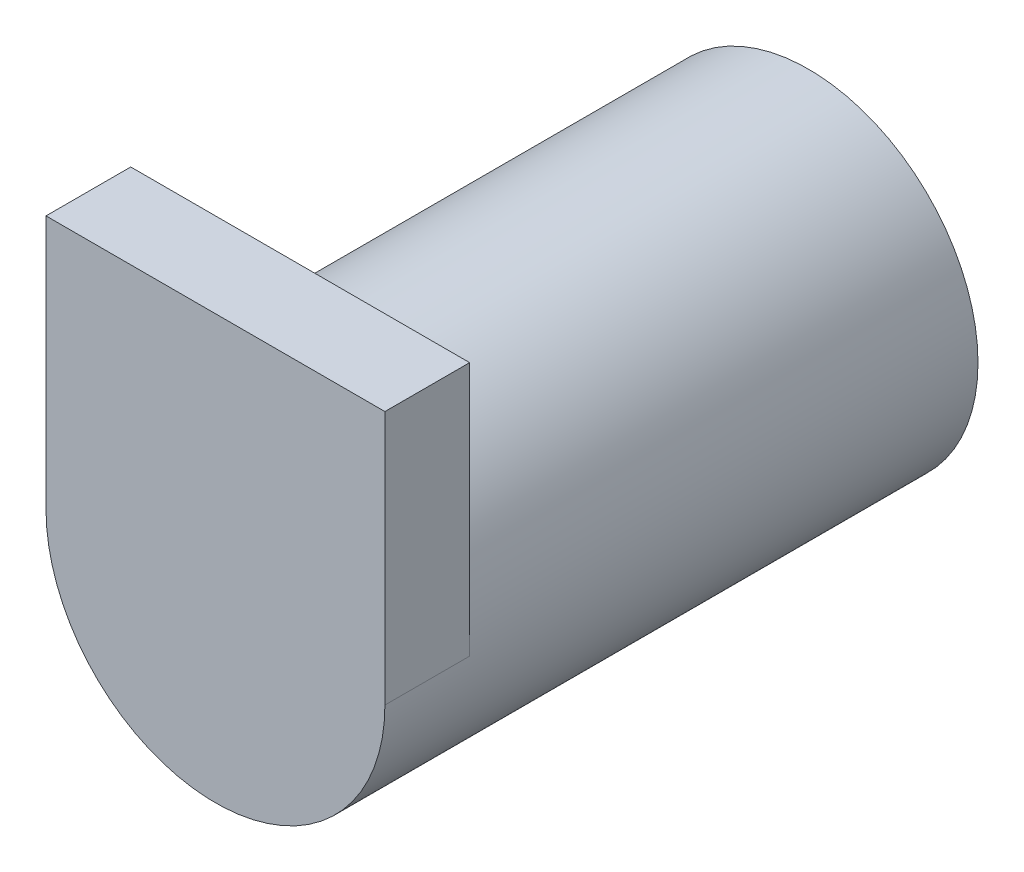
SolidWorks part; units mm, degrees
material "1023 Carbon Steel Sheet (SS)"
ref_plane "Front" through (0, 0, 0) normal (0, 0, 1) x (1, 0, 0)
ref_plane "Top" through (0, 0, 0) normal (0, 1, 0) x (1, 0, 0)
ref_plane "Right" through (0, 0, 0) normal (1, 0, 0) x (0, 0, -1)
sketch "Sketch1" plane through (0, 0, 0) normal (0, 0, 1) x (1, 0, 0)
  circle A0 centre (0, 0) radius 25.4
  dimension "D1" = 50.8
extrude "Boss-Extrude1" add sketch "Sketch1" along normal blind 76.2
sketch "Sketch2" plane through (0, 0, 76.2) normal (0, 0, 1) x (1, 0, 0)
  line L1 (-25.4, 0) -> (25.4, 0)
  line L2 (-25.4, 0) -> (-25.4, 38.1)
  line L3 (-25.4, 38.1) -> (25.4, 38.1)
  line L4 (25.4, 0) -> (25.4, 38.1)
  circle A1 centre (0, 0) radius 25.4
  circle A2 centre (0, 0) radius 25.4
  circle M2 centre (0, 0) radius 25.4
  dimension "D2" = 38.1
  dimension "D1" = 0
extrude "Boss-Extrude2" add sketch "Sketch2" along normal blind 12.7 contours L1 M2 | L1 M2 | L4 L3 L2 M2
sketch "Sketch3" plane through (0, 0, 0) normal (0, 0, -1) x (-1, 0, 0)
  circle A0 centre (0, 0) radius 3.175
  dimension "D1" = 6.35
extrude "Boss-Extrude3" add sketch "Sketch3" along normal blind 12.7
